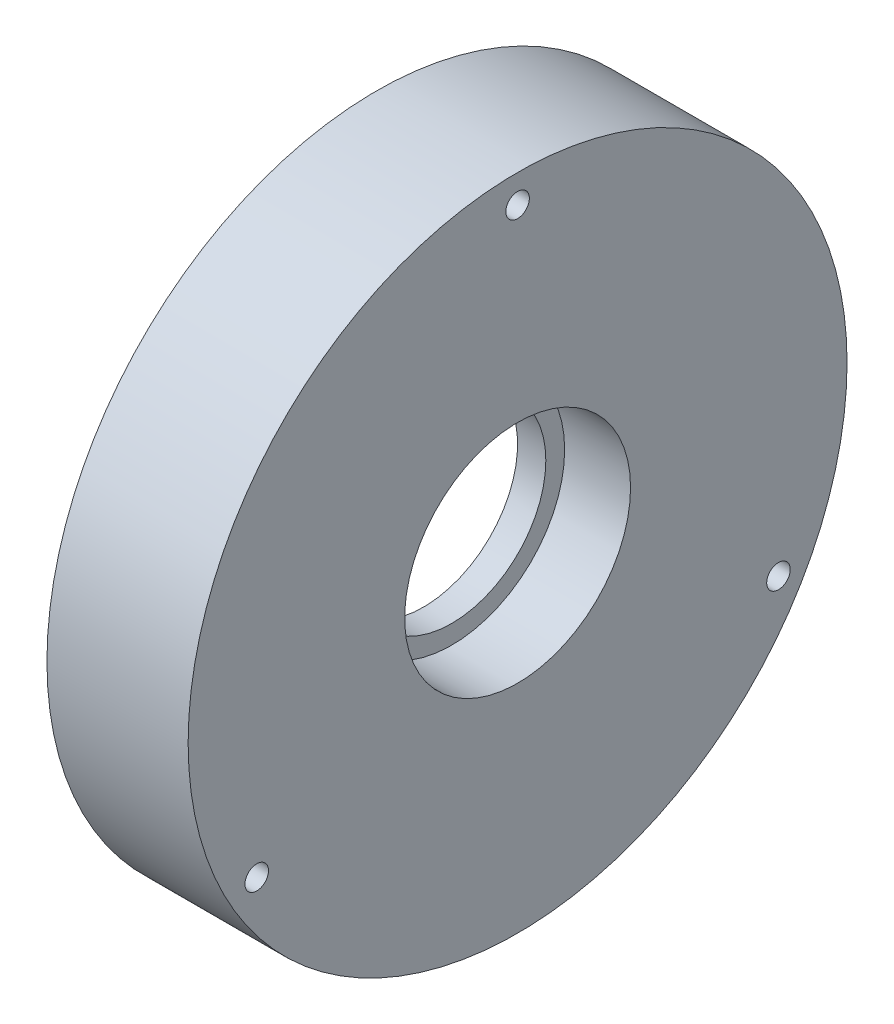
SolidWorks part; units mm, degrees
ref_plane "Plane1" through (0, 0, 0) normal (0, 0, 1) x (1, 0, 0)
ref_plane "Plane2" through (0, 0, 0) normal (0, 1, 0) x (1, 0, 0)
ref_plane "Plane3" through (0, 0, 0) normal (1, 0, 0) x (0, 0, -1)
sketch "HoldingSke" plane through (0, 0, 0) normal (0, 1, 0) x (1, 0, 0)
  line L0 (0, 0) -> (1.1472, -1.6383)
  line L1 (-15, 0) -> (100, 0) construction
  line L2 (0, 0) -> (-2.1039, 2.3779)
  line L3 (0, 0) -> (-11.863, 4.5341)
  line L4 (0, 0) -> (4.9534, 7.0742)
  line L5 (0, 0) -> (-23.7986, -8.8762)
  line L6 (0, 0) -> (-10.5278, -7.1032)
  line L7 (-2.1039, 2.3779) -> (3.3635, 27.1825)
  line L8 (-76.2, 2.8779) -> (-54.61, 2.8779)
  line L9 (-71.009, 38.7566) -> (-53.1078, 45.2721)
  line L10 (-76.2, 71.12) -> (104.1128, 71.12)
  line L11 (0, 0) -> (-5, 0)
  line L12 (-76.2, 101.6) -> (-76.181, 101.6)
  line L13 (24.9733, 27.94) -> (52.9518, 28.4284)
  line L14 (24.9733, 27.94) -> (24.9743, 27.94)
  line L15 (24.9733, 27.94) -> (100.4006, 29.5858)
  circle A0 centre (0, 0) radius 17.5
  circle A1 centre (0, 0) radius 12.7
  circle A2 centre (0, 0) radius 12.7
  dimension "MHD" = 25.4
  dimension "Hub_dia" = 25.4
  dimension "Diameter" = 35
  dimension "Num_teeth" = 55
  dimension "Pitch" = 2
  dimension "Overall_len" = 25.4
  dimension "Show_teeth" = 55
  dimension "Thickness" = 12.7
  dimension "OAL" = 25.4001
  dimension "T_dim" = 21.59
  dimension "Ap" = 20
  dimension "H" = 19.05
  dimension "Pitch_radius" = 180.3128
  dimension "Width" = 5
  dimension "Backlash" = 0.019
  dimension "Addendum_fac" = 1
  dimension "Dedendum_fac" = 1.25
  dimension "Clearance_fac" = 0.25
  dimension "Dedendum_add" = 0.001
  dimension "Module" = 0.5
sketch "BasProSke" plane through (0, 0, 0) normal (0, 1, 0) x (1, 0, 0)
  line L0 (-10, 0) -> (60, 0) construction
  line L1 (0, 13.25) -> (0, 17.5)
  line L2 (0, 13.25) -> (5, 13.25)
  line L3 (5, 13.25) -> (5, 17.5)
  line L4 (5, 17.5) -> (0, 17.5)
  dimension "Diameter" = 35
  dimension "Thickness" = 5
  dimension "Inside_diameter" = 26.5
revolve "Base-Revolve" add sketch "BasProSke" angle 360 about L0
sketch "TooCutSke" plane through (0, 0, 0) normal (1, 0, 0) x (0, 0, -1)
  line L3 (0.4401, 13.743) -> (0.4401, 53.6633) construction
  line L4 (0, 0) -> (0, 59.563) construction
  line L5 (0, 0) -> (-3.9007, 68.2161) construction
  line L6 (-5.9882, 11.3053) -> (37.1172, 13.7701) construction
  circle A0 centre (0, 0) radius 13.75 construction
  circle A1 centre (0, 0) radius 14.376 construction
  circle A2 centre (0, 0) radius 11.6287 construction
  circle A3 centre (0, 0) radius 13.2246 construction
  arc A4 (0.6177, 13.2102) -> (0.1634, 14.3751) centre (-5.9882, 11.3053) ccw
  arc A5 (0.6177, 13.2102) -> (-0.6177, 13.2102) centre (0, 0) ccw
  arc A6 (0.1634, 14.3751) -> (-0.1634, 14.3751) centre (0, 0) ccw
  arc A7 (-0.1634, 14.3751) -> (-0.6177, 13.2102) centre (5.9882, 11.3053) ccw
  dimension "Pitch_dia" = 27.5
  dimension "Base_dia" = 23.2574
  dimension "Root_dia" = 28.752
  dimension "Overcut_dia" = 26.4492
  dimension "Flank_rad" = 6.875
  dimension "Half_ang" = 3.273
  dimension "Half_CT" = 0.4401
extrude "ToothCut" cut sketch "TooCutSke" along normal through all
fillet "Breaks" [suppressed] radius 0.05
fillet "RootFillets" [suppressed] radius 0.126
pattern_circular "TeethCuts" count 55 every 6.545 about axis through (-10, 0, 0) along (1, 0, 0) of "RootFillets", "Breaks", "ToothCut"
sketch "Sketch1" plane through (5, 0, 0) normal (1, 0, 0) x (0, 0, -1)
  circle A0 centre (0, 0) radius 17.5
  circle A1 centre (0, 0) radius 5
  dimension "D1" = 10
extrude "Boss-Extrude1" add sketch "Sketch1" along normal blind 2.5
sketch "Sketch2" plane through (5, 0, 0) normal (-1, 0, 0) x (0, 0, 1)
  circle A0 centre (0, 0) radius 5
  circle A1 centre (0, 0) radius 7.75
  dimension "D1" = 10
  dimension "D2" = 15.5
extrude "Boss-Extrude2" add sketch "Sketch2" along normal blind 2.5
sketch "Sketch3" plane through (7.5, 0, 0) normal (1, 0, 0) x (0, 0, -1)
  circle A0 centre (0, 0) radius 6
  dimension "D1" = 12
extrude "Cut-Extrude1" cut sketch "Sketch3" against normal blind 3.5
hole_wizard "M1.6 Tapped Hole1" positions "Sketch5" profile "Sketch6" tap size "M1.6" standard "ISO" end condition through all
sketch "Sketch5" plane through (7.5, 0, 0) normal (1, 0, 0) x (0, 0, -1)
  line L2 (0, 19.3966) -> (0, 0) construction
  point P0 (0, 16)
  dimension "D1" = 16
cosmetic thread "Hole Thread1" parameters "D2"=1.6
sketch "Sketch6" plane through (7.5, 16, 0) normal (0, 1, 0) x (0, 0, -1)
  line L0 (0, 0) -> (0, 7.5)
  line L1 (0, 7.5) -> (0.625, 7.5)
  line L2 (0.625, 7.5) -> (0.625, 0)
  line L5 (0.625, 0) -> (0, 0)
  line L11 (0, -6.35) -> (0, 107.95) construction
  dimension "Thru Tap Drill Dia." = 1.25
  dimension "Thru Tap Drill Depth" = 7.5
pattern_circular "CirPattern1" count 3 over 360 about axis through (0, 0, 0) along (1, 0, 0) of "M1.6 Tapped Hole1"
equation "' \"Module@HoldingSke\" = 6.35"
equation "' \"Num_teeth@HoldingSke\" = 24"
equation "' \"Ap@HoldingSke\" =  14.5"
equation "' \"Ap@HoldingSke\" = 14.5"
equation "' \"Width@HoldingSke\" = 12"
equation "' \"Diameter@HoldingSke\" = 8 * 25.4"
equation "' \"Show_teeth@HoldingSke\" = 100"
equation "' \"Backlash@HoldingSke\" = 0.009 * 25.4"
equation "' \"Addendum_fac@HoldingSke\" = 1.0"
equation "' \"Dedendum_fac@HoldingSke\" = 1.25"
equation "' \"Dedendum_add@HoldingSke\" = 0.00005 * 25.4"
equation "' \"Clearance_fac@HoldingSke\" = 0.25"
equation "\"Pitch@HoldingSke\" = 1 / \"Module@HoldingSke\" "
equation "\"Overcut_dia@TooCutSke\" = (\"Num_teeth@HoldingSke\" - 2 * \"Addendum_fac@HoldingSke\") / \"Pitch@HoldingSke\" - 0.002 * 25.4"
equation "\"Pitch_dia@TooCutSke\" = \"Num_teeth@HoldingSke\" / \"Pitch@HoldingSke\""
equation "\"Base_dia@TooCutSke\" = \"Num_teeth@HoldingSke\" / \"Pitch@HoldingSke\" * cos((\"Ap@HoldingSke\"  * 3.14159265 / 180)) * 0.90"
equation "\"Root_dia@TooCutSke\" = \"Num_teeth@HoldingSke\"  / \"Pitch@HoldingSke\" + 2 *  \"Dedendum_fac@HoldingSke\"/ \"Pitch@HoldingSke\" + \"Dedendum_add@HoldingSke\" * 2"
equation "\"Half_ang@TooCutSke\" = 180 / \"Num_teeth@HoldingSke\""
equation "\"Half_CT@TooCutSke\" = \"Num_teeth@HoldingSke\" / \"Pitch@HoldingSke\" * sin((3.14159265 / 2 / \"Num_teeth@HoldingSke\")) / 2 + 10 * \"Backlash@HoldingSke\" / 4"
equation "\"Flank_rad@TooCutSke\" = \"Num_teeth@HoldingSke\" / \"Pitch@HoldingSke\" / 4"
equation "\"Radius@RootFillets\"= \"Clearance_fac@HoldingSke\" / \"Pitch@HoldingSke\" + \"Dedendum_add@HoldingSke\""
equation "\"Break_rad@Breaks\" = 0.02 / \"Pitch@HoldingSke\" * 5"
equation "\"Num_teeth@TeethCuts\" = int( \"Show_teeth@HoldingSke\" ) + 1"
equation "\"Num_teeth@TeethCuts\" = ((sgn( \"Num_teeth@TeethCuts\" - \"Num_teeth@HoldingSke\" )-1)*( \"Num_teeth@TeethCuts\" - \"Num_teeth@HoldingSke\" ))/-2+ \"Num_teeth@HoldingSke\""
equation "\"Num_teeth@TeethCuts\" = ((sgn( \"Num_teeth@TeethCuts\" - 2.0)+1)*( \"Num_teeth@TeethCuts\" - 2.0))/2 +2.0"
equation "\"Angle@TeethCuts\" = 360.0 / \"Num_teeth@HoldingSke\""
equation "\"Diameter@BasProSke\" = \"Num_teeth@HoldingSke\"  / \"Pitch@HoldingSke\" + 2 *  \"Dedendum_fac@HoldingSke\"/ \"Pitch@HoldingSke\" + \"Dedendum_add@HoldingSke\" * 2 + 0.002 * 25.4"
equation "\"Diameter@BasProSke\" = ((sgn( \"Diameter@BasProSke\"  - \"Diameter@HoldingSke\" )+1)*( \"Diameter@BasProSke\"  - \"Diameter@HoldingSke\" ))/2 + \"Diameter@HoldingSke\""
equation "\"Inside_diameter@BasProSke\" =  (\"Num_teeth@HoldingSke\" - 2 * \"Addendum_fac@HoldingSke\") / \"Pitch@HoldingSke\" "
equation "\"Thickness@BasProSke\"  = \"Width@HoldingSke\""
